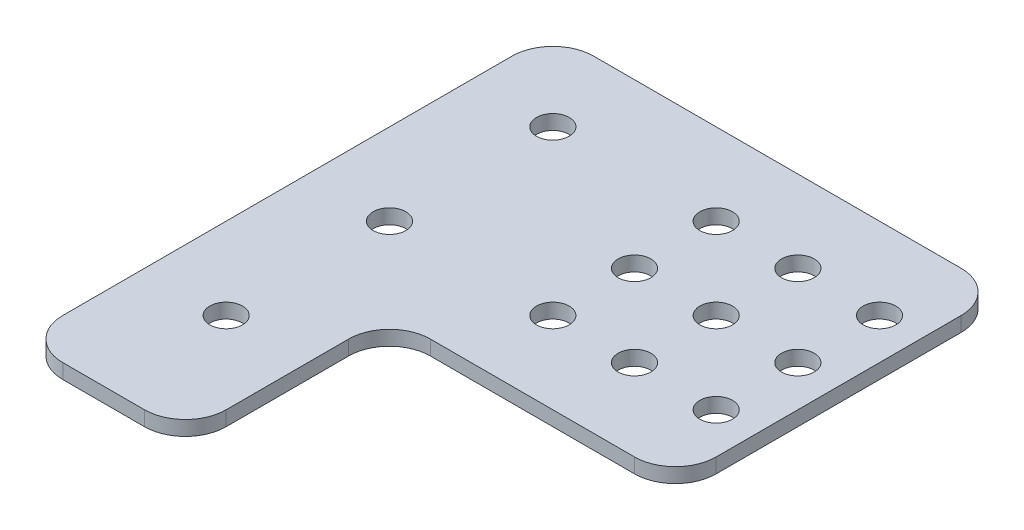
SolidWorks part; units mm, degrees
ref_plane "Front Plane" through (0, 0, 0) normal (0, 0, 1) x (1, 0, 0)
ref_plane "Top Plane" through (0, 0, 0) normal (0, 1, 0) x (1, 0, 0)
ref_plane "Right Plane" through (0, 0, 0) normal (1, 0, 0) x (0, 0, -1)
sketch "Sketch1" plane through (0, 0, 0) normal (0, 1, 0) x (1, 0, 0)
  line B0 (25.4, 114.3) -> (0, 114.3)
  line B1 (0, 114.3) -> (0, 0)
  line B2 (0, 0) -> (25.4, 0)
  line B3 (25.4, 0) -> (25.4, 31.75)
  line B4 (25.4, 31.75) -> (69.85, 31.75)
  line B5 (69.85, 31.75) -> (69.85, 82.55)
  line B6 (69.85, 82.55) -> (25.4, 82.55)
  line B7 (25.4, 82.55) -> (25.4, 114.3)
  circle B8 centre (12.7, 95.25) radius 2.54
  circle B9 centre (12.7, 69.85) radius 2.54
  circle B10 centre (12.7, 44.45) radius 2.54
  circle B11 centre (12.7, 19.05) radius 2.54
  circle B12 centre (38.1, 69.85) radius 2.54
  circle B13 centre (50.8, 69.85) radius 2.54
  circle B14 centre (63.5, 69.85) radius 2.54
  circle B15 centre (50.8, 57.15) radius 2.54
  circle B16 centre (63.5, 57.15) radius 2.54
  circle B17 centre (50.8, 44.45) radius 2.54
  circle B18 centre (63.5, 44.45) radius 2.54
  circle B19 centre (38.1, 57.15) radius 2.54
  circle B20 centre (38.1, 44.45) radius 2.54
sketch_block_instance "Block-2x2_DriveBase_Guessest-1"
sketch_block "Block-2x2_DriveBase_Guessest" parameters "D5"=5.08, "D11"=5.08, "D1"=50.8, "D2"=31.75, "D3"=31.75, "D4"=69.85, "D6"=12.7, "D7"=19.05, "D8"=25.4, "D9"=12.7, "D10"=31.75, "D12"=12.7, "D13"=12.7
extrude "Boss-Extrude1" add sketch "Sketch1" along normal blind 2.286
sketch "Sketch2" plane through (0, 2.286, 0) normal (0, 1, 0) x (1, 0, 0)
  line L1 (0, 114.3) -> (25.4, 114.3)
  line L2 (0, 114.3) -> (0, 82.55)
  line L3 (0, 82.55) -> (25.4, 82.55)
  line L4 (25.4, 114.3) -> (25.4, 82.55)
extrude "Cut-Extrude1" cut sketch "Sketch2" against normal blind 2.54
fillet "Fillet1" radius 6.35 6 edges at (69.85, 1.143, -82.55) (69.85, 1.143, -31.75) (25.4, 1.143, -31.75) (25.4, 1.143, 0) (0, 1.143, 0) (0, 1.143, -82.55)
